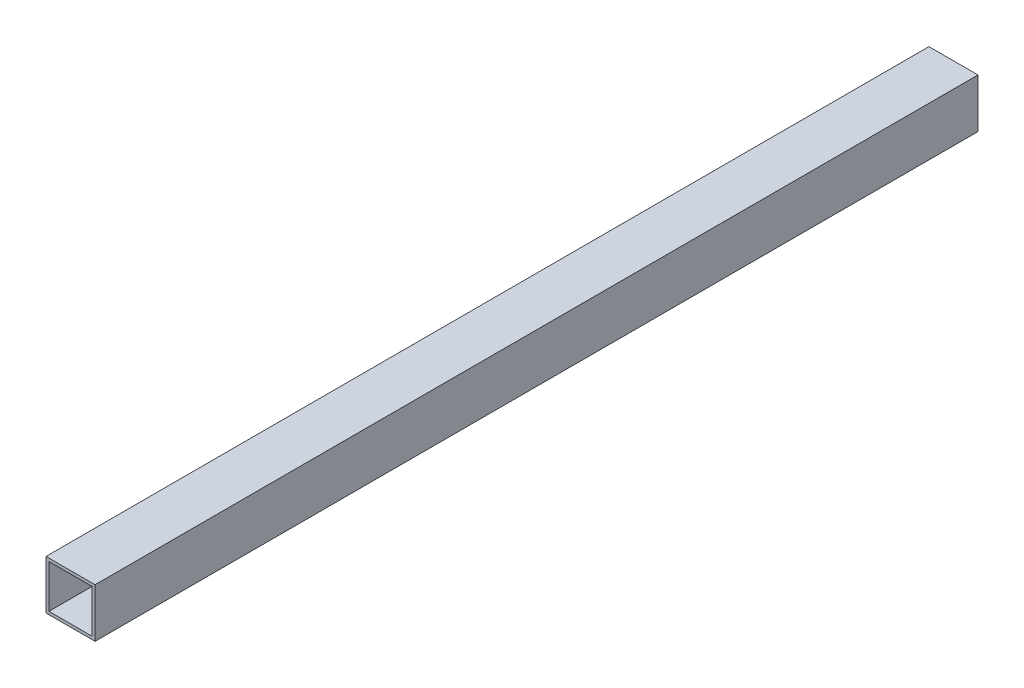
SolidWorks part; units mm, degrees
material "1.5714 (16NiCr4)"
ref_plane "Alzado" through (0, 0, 0) normal (0, 0, 1) x (1, 0, 0)
ref_plane "Planta" through (0, 0, 0) normal (0, 1, 0) x (1, 0, 0)
ref_plane "Vista lateral" through (0, 0, 0) normal (1, 0, 0) x (0, 0, -1)
sketch "Croquis1" plane through (0, 0, 0) normal (0, 0, 1) x (1, 0, 0)
  line L0 (-22, -22) -> (-22, 22)
  line L1 (-25, -25) -> (25, -25)
  line L2 (-25, -25) -> (-25, 25)
  line L3 (-25, 25) -> (25, 25)
  line L4 (25, -25) -> (25, 25)
  line L5 (-25, -25) -> (25, 25) construction
  line L6 (-25, 25) -> (25, -25) construction
  line L7 (-22, 22) -> (22, 22)
  line L8 (22, -22) -> (22, 22)
  line L9 (-22, -22) -> (22, -22)
  point P0 (0, 0)
  dimension "D1" = 50
  dimension "D2" = 50
  dimension "D3" = 3
extrude "Saliente-Extruir1" add sketch "Croquis1" along normal mid plane 900
